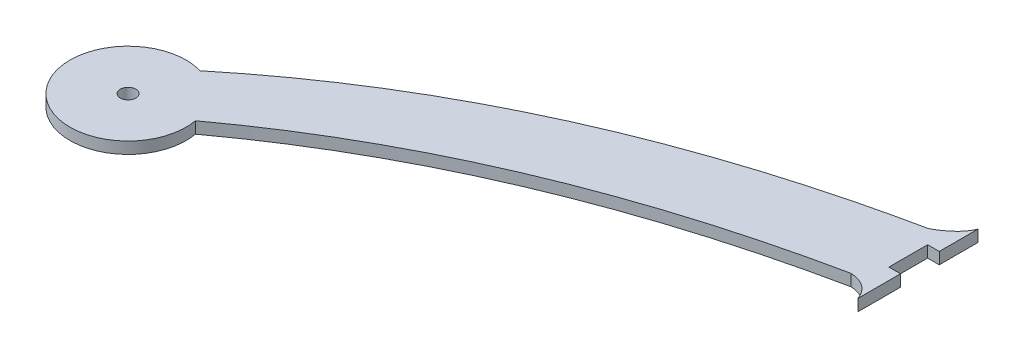
SolidWorks part; units mm, degrees
material "Acrylic (Medium-high impact)"
ref_plane "Front Plane" through (0, 0, 0) normal (0, 0, 1) x (1, 0, 0)
ref_plane "Top Plane" through (0, 0, 0) normal (0, 1, 0) x (1, 0, 0)
ref_plane "Right Plane" through (0, 0, 0) normal (1, 0, 0) x (0, 0, -1)
sketch "Sketch3" plane through (0, 0, 0) normal (0, 1, 0) x (1, 0, 0)
  line L0 (0, 20) -> (0, 0)
  line L1 (135.7457, 60) -> (135.7457, 80)
  line L2 (135.7457, 75) -> (132.7457, 75)
  line L3 (132.7457, 75) -> (132.7457, 65)
  line L4 (132.7457, 65) -> (135.7457, 65)
  line L5 (135.7457, 80) -> (135.7457, 85)
  line L6 (135.7457, 60) -> (135.7457, 54)
  circle A0 centre (-4.2, 5.6) radius 15
  spline S0 degree 3 poles (0, 0) (34.5448, 28.4477) (77.6393, 48.0198) (129.2835, 58.7164) knots 0 0 0 0 0.960222 0.960222 0.960222 0.960222
  spline S1 degree 3 poles (0, 20) (34.5448, 48.4477) (77.6393, 68.0198) (129.2835, 78.7164) knots 0 0 0 0 0.960222 0.960222 0.960222 0.960222
  spline S2 degree 2 poles (135.7457, 85) (134.393, 81.5429) (129.2835, 78.7164) knots 0 0 0 1 1 1
  spline S3 degree 2 poles (135.7457, 54) (134.1884, 58.3472) (129.2835, 58.7164) knots 0 0 0 1 1 1
  dimension "D6" = 5
  dimension "D4" = 30
  dimension "D10" = 7
  dimension "D16" = 9.1911
  dimension "D17" = 8.5303
  dimension "D2" = 60
  dimension "D3" = 135.7457
  dimension "D5" = 20
  dimension "D7" = 1.2836
  dimension "D8" = 5
  dimension "D9" = 15
  dimension "D11" = 3
  dimension "D12" = 10
  dimension "D15" = 6
extrude "Boss-Extrude2" add sketch "Sketch3" along normal blind 3 contours S0 L0 A0 | S1 A0 S0 L1 | L0 S0 A0
sketch "Sketch4" plane through (0, 3, 0) normal (0, 1, 0) x (1, 0, 0)
  circle A0 centre (-4.2, 5.6) radius 2
  dimension "D1" = 4
extrude "Cut-Extrude2" cut sketch "Sketch4" against normal blind 3
